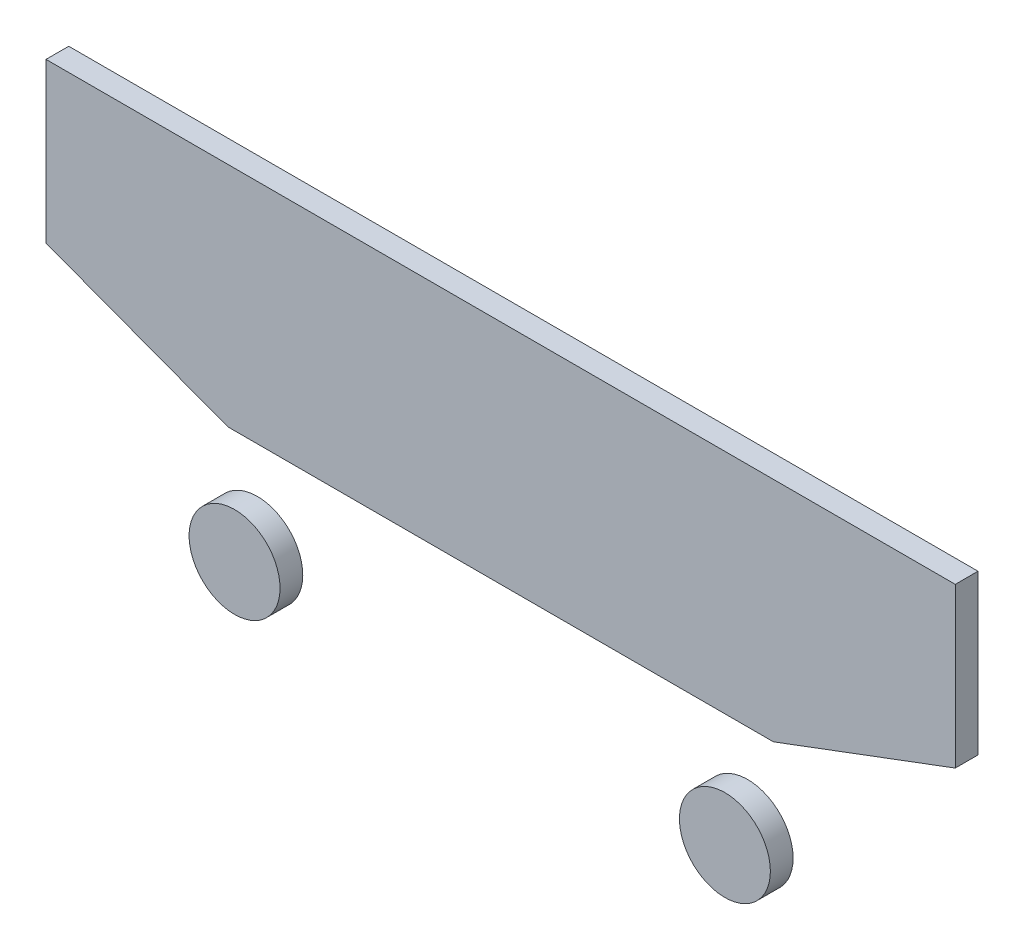
SolidWorks part; units mm, degrees
ref_plane "Front Plane" through (0, 0, 0) normal (0, 0, 1) x (1, 0, 0)
ref_plane "Top Plane" through (0, 0, 0) normal (0, 1, 0) x (1, 0, 0)
ref_plane "Right Plane" through (0, 0, 0) normal (1, 0, 0) x (0, 0, -1)
sketch "Sketch1" plane through (0, 0, 0) normal (0, 0, 1) x (1, 0, 0)
  line L0 (158.5226, 85) -> (-41.4774, 85)
  line L3 (118.5226, 35) -> (-1.4774, 35)
  line L7 (-41.4774, 85) -> (-41.4774, 50)
  line L8 (-41.4774, 50) -> (-1.4774, 35)
  line L9 (118.5226, 35) -> (158.5226, 50)
  line L10 (158.5226, 50) -> (158.5226, 85)
  line L13 (-45.4173, 0) -> (50.6061, 0) construction
  line L14 (0, 10) -> (107.8504, 10) construction
  circle A0 centre (0, 10) radius 10
  circle A1 centre (107.8504, 10) radius 10
  point P0 (378.2301, 86.9254)
  dimension "Dia 1" = 20
  dimension "Dia 2" = 20
  dimension "bottom height" = 25
  dimension "wheel axis to end 1" = 41.4774
  dimension "Bottom height 2" = 25
  dimension "wheel axis to end 2" = 50.6722
  dimension "height 1" = 50
  dimension "height 2" = 50
  dimension "slope dist 1" = 40
  dimension "slope dist 2" = 40
  dimension "arbetrary" = 50
  dimension "length" = 200
extrude "Boss-Extrude1" add sketch "Sketch1" along normal blind 5
